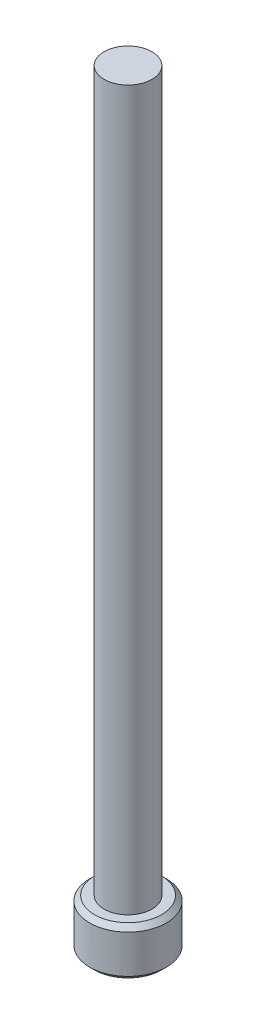
SolidWorks part; units mm, degrees
ref_plane "Front Plane" through (0, 0, 0) normal (0, 0, 1) x (1, 0, 0)
ref_plane "Top Plane" through (0, 0, 0) normal (0, 1, 0) x (1, 0, 0)
ref_plane "Right Plane" through (0, 0, 0) normal (1, 0, 0) x (0, 0, -1)
sketch "Sketch1" plane through (0, 0, 0) normal (0, 1, 0) x (1, 0, 0)
  circle A0 centre (0, 0) radius 2.5
extrude "Boss-Extrude1" add sketch "Sketch1" along normal blind 75
sketch "Sketch3" plane through (0, 0, 0) normal (0, 0, 1) x (1, 0, 0)
  line L0 (0, 0) -> (-4, 0)
  line L1 (-2.5, 0) -> (2.5, 0) construction
  line L2 (-4, 0) -> (-4, -5)
  line L3 (0, 0) -> (0, 12.6087) construction
  line L4 (-4, -5) -> (0, -5)
  line L5 (0, -5) -> (0, 0)
revolve "Revolve1" add sketch "Sketch3" angle 360 about L5
sketch "Sketch4" plane through (0, 0, 0) normal (0, 1, 0) x (1, 0, 0)
  line L1 (2.8868, 0) -> (1.4434, 2.5)
  line L2 (1.4434, 2.5) -> (-1.4434, 2.5)
  line L3 (-1.4434, 2.5) -> (-2.8868, 0)
  line L4 (-2.8868, 0) -> (-1.4434, -2.5)
  line L5 (-1.4434, -2.5) -> (1.4434, -2.5)
  line L6 (1.4434, -2.5) -> (2.8868, 0)
  circle A0 centre (0, 0) radius 2.5 construction
extrude "Cut-Extrude1" cut sketch "Sketch4" against normal blind 30 from offset 1 offset against normal yes
chamfer "Chamfer1" distance 0.5 angle 45 2 edges at (0, -5, -4) (0, 0, -4)
